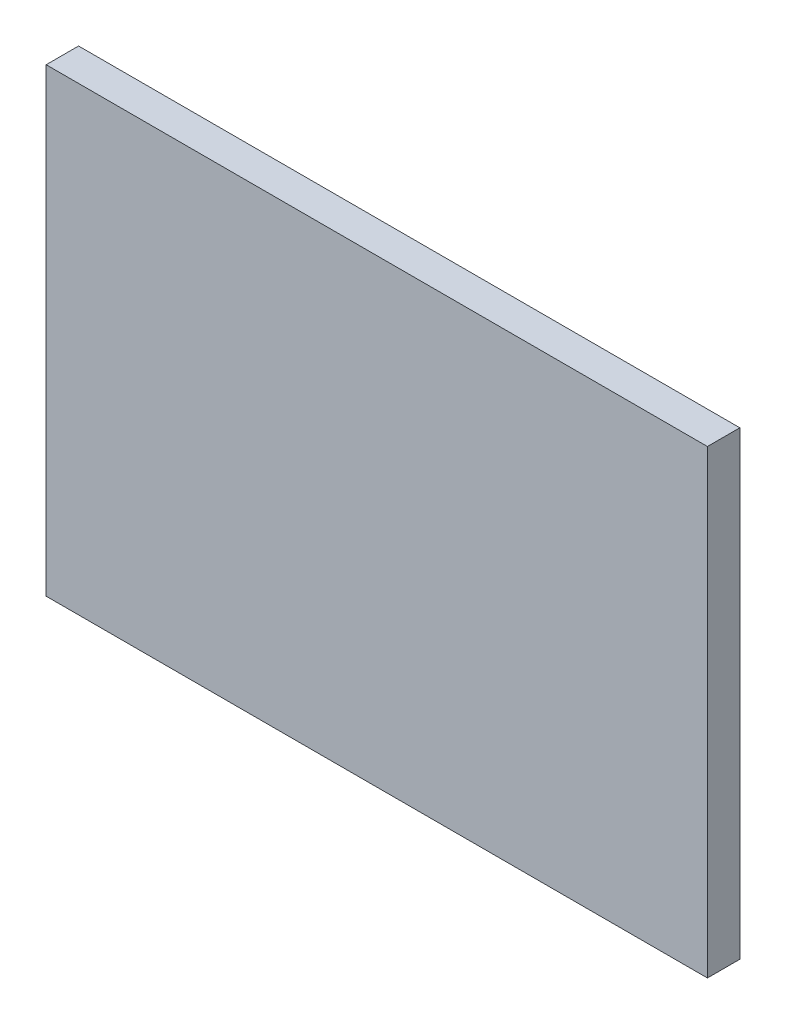
SolidWorks part; units mm, degrees
ref_plane "Front Plane" through (0, 0, 0) normal (0, 0, 1) x (1, 0, 0)
ref_plane "Top Plane" through (0, 0, 0) normal (0, 1, 0) x (1, 0, 0)
ref_plane "Right Plane" through (0, 0, 0) normal (1, 0, 0) x (0, 0, -1)
sketch "Sketch1" plane through (0, 0, 0) normal (0, 0, 1) x (1, 0, 0)
  line L1 (-51, 35.5) -> (51, 35.5)
  line L2 (-51, 35.5) -> (-51, -35.5)
  line L3 (-51, -35.5) -> (51, -35.5)
  line L4 (51, 35.5) -> (51, -35.5)
  dimension "D1" = 102
  dimension "D2" = 71
  dimension "D3" = 35.5
  dimension "D4" = 51
extrude "Boss-Extrude1" add sketch "Sketch1" along normal blind 5
